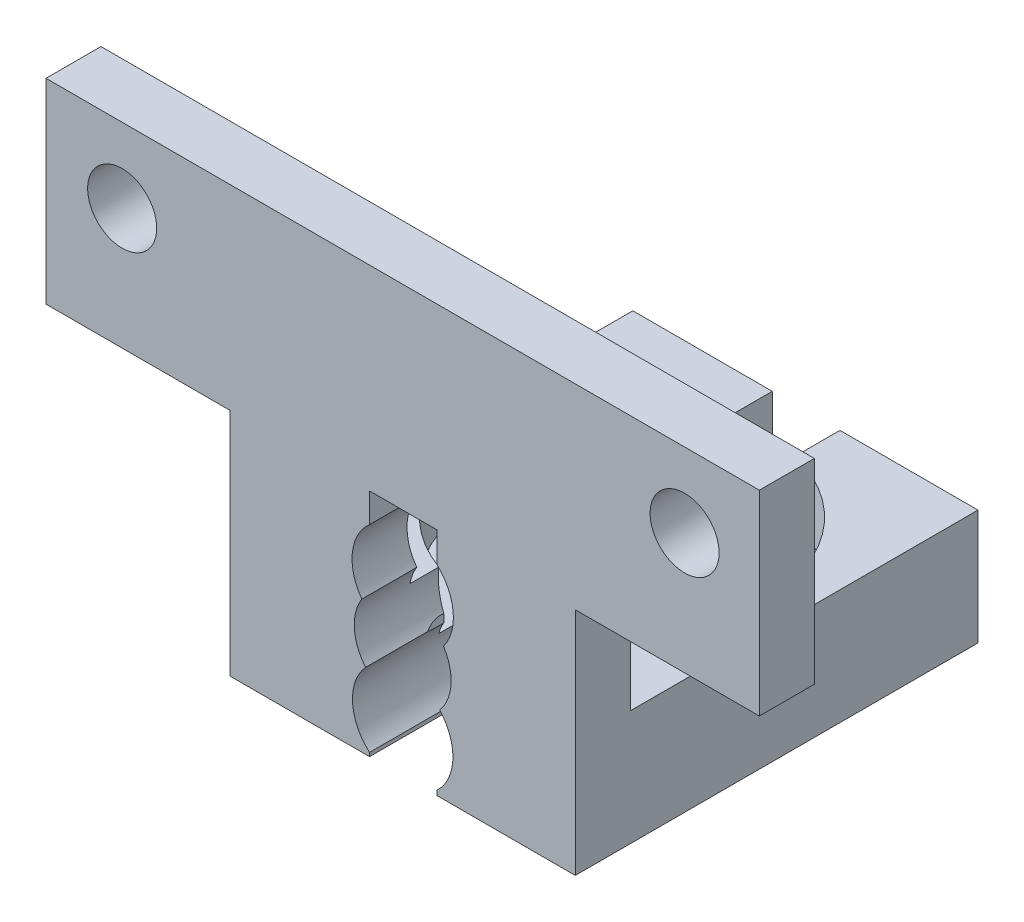
SolidWorks part; units mm, degrees
ref_plane "前基準面" through (0, 0, 0) normal (0, 0, 1) x (1, 0, 0)
ref_plane "上基準面" through (0, 0, 0) normal (0, 1, 0) x (1, 0, 0)
ref_plane "右基準面" through (0, 0, 0) normal (1, 0, 0) x (0, 0, -1)
sketch "草圖1" plane through (0, 0, 0) normal (0, 1, 0) x (1, 0, 0)
  line L1 (-35, 21.5) -> (35, 21.5)
  line L2 (-35, 21.5) -> (-35, -21.5)
  line L3 (-35, -21.5) -> (35, -21.5)
  line L4 (35, 21.5) -> (35, -21.5)
  line L5 (-35, 21.5) -> (35, -21.5) construction
  line L6 (-35, -21.5) -> (35, 21.5) construction
  point P0 (0, 0)
  dimension "D1" = 70
  dimension "D2" = 43
extrude "填料-伸長1" add sketch "草圖1" along normal blind 10
sketch "草圖8" plane through (0, 0, 21.5) normal (0, 0, 1) x (1, 0, 0)
  line L0 (-1035, 5) -> (48965, 5) construction
  line L1 (-35, 10) -> (-35, 0) construction
  line L2 (0, -990) -> (0, 49010) construction
  line L3 (-35, 10) -> (35, 10) construction
  line L4 (35, 10) -> (35, 0) construction
  line L5 (-12.38, 10) -> (12.5, 10)
  line L6 (-12.38, 10) -> (-12.38, 5)
  line L7 (-12.38, 5) -> (12.5, 5)
  line L8 (12.5, 10) -> (12.5, 5)
  point P5 (-35, 5)
  point P10 (0, 10)
  dimension "D1" = 24.88
  dimension "D2" = 22.5
extrude "除料-伸長4" cut sketch "草圖8" against normal through all
sketch "草圖11" plane through (0, 5, 0) normal (0, 1, 0) x (1, 0, 0)
  line L0 (0.06, -978.5) -> (0.06, 49021.5) construction
  line L1 (-12.38, 21.5) -> (12.5, 21.5) construction
  line L2 (-1012.38, 0) -> (48987.62, 0) construction
  line L3 (-12.38, 21.5) -> (-12.38, -21.5) construction
  circle A0 centre (0.06, 0) radius 12.45
  point P5 (0.06, 21.5)
  point P10 (-12.38, 0)
  dimension "D1" = 24.9
extrude "伸長-薄件1" add sketch "草圖11" along normal blind 5 and the other way blind 2 thin
sketch "草圖14" plane through (0, 5, 0) normal (0, 1, 0) x (1, 0, 0)
  line L0 (0.06, -20.45) -> (12.5, -20.45)
  line L1 (12.5, -16.2311) -> (12.5, -21.5) construction
  line L2 (12.5, -20.45) -> (12.5, -21.5)
  line L3 (12.5, -21.5) -> (-12.38, -21.5)
  line L4 (-12.38, -21.5) -> (-12.38, -20.45)
  line L5 (-12.38, -16.2311) -> (-12.38, -21.5) construction
  line L6 (-12.38, -20.45) -> (0.06, -20.45)
  arc A0 (-12.38, -16.2311) -> (12.5, -16.2311) centre (0.06, 0) ccw construction
extrude "除料-伸長6" cut sketch "草圖14" against normal blind 5
sketch "草圖15" plane through (0, 5, 0) normal (0, 1, 0) x (1, 0, 0)
  line L0 (0.06, 20.45) -> (12.5, 20.45)
  line L1 (12.5, 21.5) -> (12.5, 16.2311) construction
  line L2 (12.5, 20.45) -> (12.5, 21.5)
  line L3 (12.5, 21.5) -> (-12.38, 21.5)
  line L4 (-12.38, 21.5) -> (-12.38, 20.45)
  line L5 (-12.38, 21.5) -> (-12.38, 16.2311) construction
  line L6 (-12.38, 20.45) -> (0.06, 20.45)
  arc A0 (12.5, 16.2311) -> (-12.38, 16.2311) centre (0.06, 0) ccw construction
extrude "除料-伸長7" cut sketch "草圖15" against normal blind 5
sketch "草圖16" plane through (0, 10, 0) normal (0, 1, 0) x (1, 0, 0)
  line L0 (0.06, -987.55) -> (0.06, 49012.45) construction
  line L2 (-2.88, 23.0979) -> (3, 23.0979)
  line L3 (-2.88, 23.0979) -> (-2.88, 12.0979)
  line L4 (-2.88, 12.0979) -> (3, 12.0979)
  line L5 (3, 23.0979) -> (3, 12.0979)
  line L6 (-2.88, 23.0979) -> (3, 12.0979) construction
  line L7 (-2.88, 12.0979) -> (3, 23.0979) construction
  arc A0 (12.5, 0.4989) -> (-12.38, 0.4989) centre (0.06, 0) ccw construction
  point P1 (0.06, 17.5979)
  point P6 (0.06, 12.45)
  dimension "D1" = 5.88
  dimension "D2" = 11
extrude "除料-伸長8" cut sketch "草圖16" against normal blind 5
sketch "草圖17" plane through (0, 10, 0) normal (0, 1, 0) x (1, 0, 0)
  line L0 (-2.88, -987.9021) -> (-2.88, 49012.0979) construction
  line L1 (3, -987.9021) -> (3, 49012.0979) construction
  line L2 (12.5, -20.45) -> (0.06, -20.45) construction
  line L3 (-2.88, -12.0979) -> (3, -12.0979)
  line L4 (-2.88, -12.0979) -> (-2.88, -20.45)
  line L5 (-2.88, -20.45) -> (3, -20.45)
  line L6 (3, -12.0979) -> (3, -20.45)
  arc A0 (-12.38, -0.4989) -> (12.5, -0.4989) centre (0.06, 0) ccw construction
extrude "除料-伸長9" cut sketch "草圖17" against normal blind 5
sketch "草圖19" plane through (0, 5, 0) normal (0, 1, 0) x (1, 0, 0)
  line L0 (-2.88, 20.2376) -> (-2.88, 20.45)
  line L1 (-12.38, 20.45) -> (12.5, 20.45) construction
  line L2 (-2.88, 20.45) -> (2.9876, 20.45)
  line L3 (2.9876, 20.45) -> (3, 20.2376)
  line L4 (3, 12.0979) -> (3, 20.2376) construction
  line L5 (3, 20.2376) -> (-2.88, 20.2376)
  arc A0 (12.5, 16.2311) -> (3, 20.2376) centre (0.06, 0) ccw construction
extrude "除料-伸長10" cut sketch "草圖19" against normal blind 5
sketch "草圖20" plane through (0, 5, 0) normal (0, 1, 0) x (1, 0, 0)
  line L0 (3, -20.2376) -> (3, -20.45)
  line L1 (12.5, -20.45) -> (-12.38, -20.45) construction
  line L2 (3, -20.45) -> (-2.8878, -20.45)
  line L3 (-2.8878, -20.45) -> (-2.88, -20.2376)
  line L4 (-2.88, -20.2376) -> (3, -20.2376)
extrude "除料-伸長11" cut sketch "草圖20" against normal blind 5
sketch "草圖21" plane through (0, 10, 0) normal (0, 1, 0) x (1, 0, 0)
  line L0 (-12.38, 21.5) -> (-35, 21.5) construction
  line L1 (-35, 21.5) -> (-35, -21.5) construction
  circle A0 centre (-25, 11.5) radius 3
  dimension "D1" = 10
  dimension "D2" = 10
  dimension "D3" = 6
extrude "除料-伸長12" cut sketch "草圖21" against normal through all
sketch "草圖22" plane through (0, 10, 0) normal (0, 1, 0) x (1, 0, 0)
  line L0 (35, 21.5) -> (12.5, 21.5) construction
  line L1 (35, -21.5) -> (35, 21.5) construction
  circle A0 centre (25, 11.5) radius 3
  dimension "D1" = 10
  dimension "D2" = 10
  dimension "D3" = 6
extrude "除料-伸長13" cut sketch "草圖22" against normal through all
sketch "草圖24" plane through (0, 5, 0) normal (0, 1, 0) x (1, 0, 0)
  circle A0 centre (0, -12.2162) radius 3.51
  dimension "D1" = 7.02
extrude "除料-伸長15" cut sketch "草圖24" along normal blind 7
sketch "草圖25" plane through (0, 0, 21.5) normal (0, 0, 1) x (1, 0, 0)
  line L1 (35, 0) -> (12.5, 0)
  line L2 (35, 0) -> (35, 10)
  line L3 (35, 10) -> (12.5, 10)
  line L4 (12.5, 0) -> (12.5, 10)
extrude "填料-伸長2" add sketch "草圖25" along normal blind 5
sketch "草圖26" plane through (0, 0, 21.5) normal (0, 0, 1) x (1, 0, 0)
  line L0 (-35, 10) -> (-35, 0) construction
  line L1 (-12.38, 0) -> (-35, 0)
  line L2 (-12.38, 0) -> (-12.38, 10)
  line L3 (-12.38, 10) -> (-35, 10)
  line L4 (-35, 0) -> (-35, 10)
extrude "填料-伸長3" add sketch "草圖26" along normal blind 5
sketch "草圖28" plane through (0, 5, 0) normal (0, 1, 0) x (1, 0, 0)
  line L0 (-2.88, -14.2226) -> (3, -14.2226)
  line L1 (3, -20.2376) -> (3, -14.0383) construction
  line L2 (3, -14.2226) -> (3, -21.7541)
  line L3 (3, -21.7541) -> (-2.88, -21.7541)
  line L4 (-2.88, -21.7541) -> (-2.88, -14.2226)
extrude "除料-伸長16" cut sketch "草圖28" against normal blind 5
sketch "草圖32" plane through (0, 5, 0) normal (0, 1, 0) x (1, 0, 0)
  line L1 (15, -16) -> (-15, -16)
  line L2 (15, -16) -> (15, 16)
  line L3 (15, 16) -> (-15, 16)
  line L4 (-15, -16) -> (-15, 16)
  line L5 (15, -16) -> (-15, 16) construction
  line L6 (15, 16) -> (-15, -16) construction
  point P0 (0, 0)
  dimension "D1" = 30
  dimension "D2" = 32
extrude "除料-伸長-薄件2" cut sketch "草圖32" along normal blind 45 and the other way blind 31 thin thin type one direction wall 40
sketch "草圖33" plane through (0, 0, 16) normal (0, 0, 1) x (1, 0, 0)
  line L1 (15, 0) -> (3, 0)
  line L2 (15, 0) -> (15, 10)
  line L3 (15, 10) -> (3, 10)
  line L4 (3, 0) -> (3, 10)
  line L5 (-2.88, 0) -> (-15, 0)
  line L6 (-2.88, 0) -> (-2.88, 10)
  line L7 (-2.88, 10) -> (-15, 10)
  line L8 (-15, 0) -> (-15, 10)
extrude "填料-伸長5" add sketch "草圖33" along normal blind 3
sketch "草圖40" plane through (0, 10, 0) normal (0, 1, 0) x (1, 0, 0)
  line L1 (3, -14.2226) -> (15, -14.2226)
  line L2 (3, -14.2226) -> (3, -19)
  line L3 (3, -19) -> (15, -19)
  line L4 (15, -14.2226) -> (15, -19)
extrude "填料-伸長7" add sketch "草圖40" along normal blind 10
sketch "草圖41" plane through (0, 10, 0) normal (0, 1, 0) x (1, 0, 0)
  line L1 (-15, -19) -> (-2.88, -19)
  line L2 (-15, -19) -> (-15, -14.2226)
  line L3 (-15, -14.2226) -> (-2.88, -14.2226)
  line L4 (-2.88, -19) -> (-2.88, -14.2226)
extrude "填料-伸長8" add sketch "草圖41" along normal blind 10
sketch "草圖42" plane through (0, 0, 14.2226) normal (0, 0, 1) x (1, 0, 0)
  circle A0 centre (0, 9.2647) radius 4.2093
extrude "除料-伸長17" cut sketch "草圖42" along normal blind 10 and the other way blind 10
sketch "草圖53" plane through (-15, 0, 0) normal (-1, 0, 0) x (0, 0, 1)
  line L1 (19, 20) -> (14.2226, 20)
  line L2 (19, 20) -> (19, 10)
  line L3 (19, 10) -> (14.2226, 10)
  line L4 (14.2226, 20) -> (14.2226, 10)
extrude "填料-伸長9" add sketch "草圖53" along normal blind 11
sketch "草圖56" plane through (15, 0, 0) normal (1, 0, 0) x (0, 0, -1)
  line L1 (-14.2226, 20) -> (-19, 20)
  line L2 (-14.2226, 20) -> (-14.2226, 0)
  line L3 (-14.2226, 0) -> (-19, 0)
  line L4 (-19, 20) -> (-19, 0)
extrude "填料-伸長10" add sketch "草圖56" along normal blind 11
sketch "草圖57" plane through (26, 0, 0) normal (1, 0, 0) x (0, 0, -1)
  line L0 (-14.2226, 0) -> (-14.2226, 20) construction
  line L1 (-14.2226, 10) -> (-19, 10)
  line L2 (-14.2226, 10) -> (-14.2226, 0)
  line L3 (-14.2226, 0) -> (-19, 0)
  line L4 (-19, 10) -> (-19, 0)
extrude "除料-伸長18" cut sketch "草圖57" against normal blind 11
sketch "草圖58" plane through (26, 0, 0) normal (1, 0, 0) x (0, 0, -1)
  line L1 (-19, 10) -> (-14.2226, 10)
  line L2 (-19, 10) -> (-19, 20)
  line L3 (-19, 20) -> (-14.2226, 20)
  line L4 (-14.2226, 10) -> (-14.2226, 20)
extrude "填料-伸長11" add sketch "草圖58" along normal blind 5
sketch "草圖59" plane through (-26, 0, 0) normal (-1, 0, 0) x (0, 0, 1)
  line L1 (19, 20) -> (14.2226, 20)
  line L2 (19, 20) -> (19, 10)
  line L3 (19, 10) -> (14.2226, 10)
  line L4 (14.2226, 20) -> (14.2226, 10)
extrude "填料-伸長12" add sketch "草圖59" along normal blind 5
sketch "草圖60" plane through (0, 20, 0) normal (0, 1, 0) x (1, 0, 0)
  line L1 (31, -19) -> (-31, -19)
  line L2 (31, -19) -> (31, -14.2226)
  line L3 (31, -14.2226) -> (-31, -14.2226)
  line L4 (-31, -19) -> (-31, -14.2226)
extrude "填料-伸長13" add sketch "草圖60" along normal blind 10
sketch "草圖61" plane through (0, 0, 14.2226) normal (0, 0, 1) x (1, 0, 0)
  line L0 (-2.88, 0) -> (-2.88, 6.1949) construction
  line L1 (3, 0) -> (-2.88, 0)
  line L2 (3, 0) -> (3, 5)
  line L3 (3, 5) -> (-2.88, 5)
  line L4 (-2.88, 0) -> (-2.88, 5)
  line L5 (-2.88, 0) -> (-2.88, 5) construction
extrude "除料-伸長19" cut sketch "草圖61" against normal blind 10
sketch "草圖69" plane through (15, 0, 0) normal (1, 0, 0) x (0, 0, -1)
  line L1 (-14.2226, 10) -> (-19, 10)
  line L2 (-14.2226, 10) -> (-14.2226, 0)
  line L3 (-14.2226, 0) -> (-19, 0)
  line L4 (-19, 10) -> (-19, 0)
extrude "填料-伸長14" add sketch "草圖69" along normal blind 16
sketch "草圖70" plane through (-15, 0, 0) normal (-1, 0, 0) x (0, 0, 1)
  line L2 (19, 0) -> (14.2226, 0)
  line L3 (19, 0) -> (19, 10)
  line L4 (19, 10) -> (14.2226, 10)
  line L5 (14.2226, 0) -> (14.2226, 10)
extrude "填料-伸長15" add sketch "草圖70" along normal blind 16
sketch "草圖83" plane through (0, 30, 0) normal (0, 1, 0) x (1, 0, 0)
  line L1 (31, -19) -> (-31, -19)
  line L2 (31, -19) -> (31, -14.2226)
  line L3 (31, -14.2226) -> (-31, -14.2226)
  line L4 (-31, -19) -> (-31, -14.2226)
extrude "填料-伸長16" add sketch "草圖83" along normal blind 29
sketch "草圖84" plane through (0, 0, 19) normal (0, 0, 1) x (1, 0, 0)
  line L0 (3, 0) -> (24.5, 0) construction
  line L1 (3, 0) -> (31, 0) construction
  line L2 (24.5, 0) -> (24.5, 27.54) construction
  line L3 (-2.88, 0) -> (-24.38, 0) construction
  line L4 (-31, 0) -> (-2.88, 0) construction
  line L5 (-24.38, 0) -> (-24.38, 27.54) construction
  dimension "D1" = 21.5
  dimension "D2" = 27.54
  dimension "D3" = 21.5
  dimension "D4" = 27.54
sketch "草圖85" plane through (0, 0, 19) normal (0, 0, 1) x (1, 0, 0)
  circle A0 centre (24.5, 30.52) radius 3
  dimension "D1" = 6
  dimension "D2" = 2.98
sketch "草圖86" plane through (0, 0, 19) normal (0, 0, 1) x (1, 0, 0)
  line L0 (24.5, 30.52) -> (-24.38, 30.52) construction
  circle A0 centre (-24.38, 30.52) radius 3
  dimension "D1" = 6
extrude "除料-伸長20" cut sketch "草圖86" against normal through all
extrude "除料-伸長21" cut sketch "草圖85" against normal through all
sketch "草圖87" plane through (0, 0, 19) normal (0, 0, 1) x (1, 0, 0)
  line L0 (-31, 0) -> (-31, 59) construction
  line L1 (31, 59) -> (-31, 59)
  line L2 (31, 59) -> (31, 37)
  line L3 (31, 37) -> (-31, 37)
  line L4 (-31, 59) -> (-31, 37)
  dimension "D1" = 22
extrude "除料-伸長22" cut sketch "草圖87" against normal through all
sketch "草圖90" plane through (0, 0, 14.2226) normal (0, 0, -1) x (-1, 0, 0)
  line L0 (-997.12, 20) -> (49002.88, 20) construction
  line L2 (15, 0) -> (31.0425, 0)
  line L3 (15, 0) -> (15, 20)
  line L4 (15, 20) -> (31.0425, 20)
  line L5 (31.0425, 0) -> (31.0425, 20)
  line L6 (-15, 0) -> (-31.0425, 0)
  line L7 (-15, 0) -> (-15, 20)
  line L8 (-15, 20) -> (-31.0425, 20)
  line L9 (-31.0425, 0) -> (-31.0425, 20)
extrude "除料-伸長23" cut sketch "草圖90" against normal blind 10
sketch "草圖91" plane through (0, 0, 19) normal (0, 0, 1) x (1, 0, 0)
  circle A0 centre (0, 14.1335) radius 4.4047
extrude "除料-伸長24" cut sketch "草圖91" against normal blind 10
sketch "草圖92" plane through (0, 0, 4.2226) normal (0, 0, 1) x (1, 0, 0)
  circle A0 centre (0, 3.6057) radius 4.3668
extrude "除料-伸長25" cut sketch "草圖92" along normal through all
